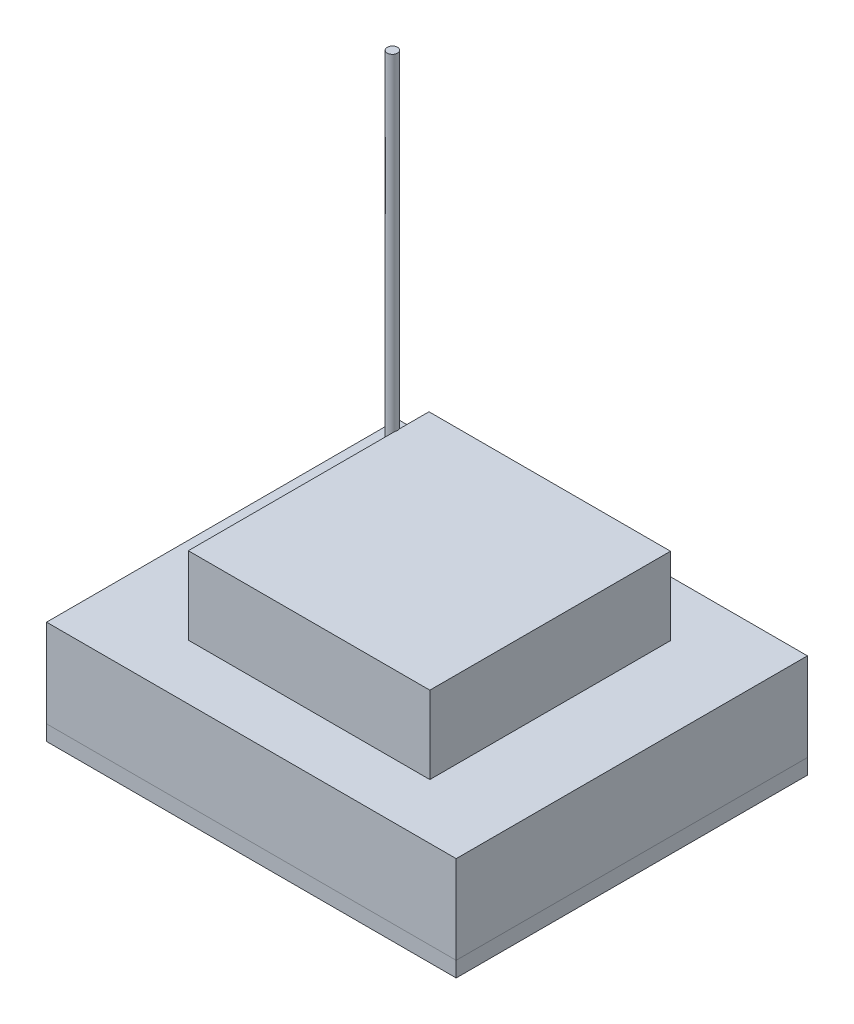
SolidWorks part; units mm, degrees
ref_plane "Front Plane" through (0, 0, 0) normal (0, 0, 1) x (1, 0, 0)
ref_plane "Top Plane" through (0, 0, 0) normal (0, 1, 0) x (1, 0, 0)
ref_plane "Right Plane" through (0, 0, 0) normal (1, 0, 0) x (0, 0, -1)
sketch "Sketch1" plane through (0, 0, 0) normal (0, 0, 1) x (1, 0, 0)
  line L1 (-509.3, -109.4835) -> (509.3, -109.4835)
  line L2 (-509.3, -109.4835) -> (-509.3, 109.4835)
  line L3 (-509.3, 109.4835) -> (509.3, 109.4835)
  line L4 (509.3, -109.4835) -> (509.3, 109.4835)
  line L5 (0, 109.4835) -> (0, -109.4835) construction
  line L6 (-509.3, 0) -> (509.3, 0) construction
  point P0 (0, 0)
  dimension "D1" = 1018.6
  dimension "D2" = 218.967
extrude "Boss-Extrude1" add sketch "Sketch1" along normal mid plane 873.5
sketch "Sketch2" plane through (0, 0, 0) normal (0, 0, 1) x (1, 0, 0)
  line L0 (509.3, 109.4835) -> (-509.3, 109.4835) construction
  line L1 (-294.3, 109.4835) -> (306.3, 109.4835)
  line L2 (-294.3, 109.4835) -> (-294.3, 302.0435)
  line L3 (-294.3, 302.0435) -> (306.3, 302.0435)
  line L4 (306.3, 109.4835) -> (306.3, 302.0435)
  line L5 (-509.3, 109.4835) -> (-509.3, -109.4835) construction
  line L6 (509.3, -109.4835) -> (509.3, 109.4835) construction
  dimension "D1" = 215
  dimension "D2" = 203
  dimension "D3" = 192.56
extrude "Boss-Extrude2" add sketch "Sketch2" along normal mid plane 598.5
sketch "Sketch3" plane through (0, 109.4835, 0) normal (0, 1, 0) x (1, 0, 0)
  line L1 (-294.3, 299.25) -> (306.3, 299.25) construction
  line L2 (-294.3, -299.25) -> (-294.3, 299.25) construction
  circle A0 centre (-306, 219.95) radius 12.7
  point P3 (-293.3, 219.95)
  dimension "D1" = 25.4
  dimension "D3" = 1
  dimension "D2" = 79.3
extrude "Boss-Extrude5" add sketch "Sketch3" along normal blind 1005.06
sketch "Sketch4" plane through (0, -109.4835, 0) normal (0, -1, 0) x (1, 0, 0)
  line L4 (-509.3, -436.75) -> (509.3, -436.75)
  line L5 (509.3, -436.75) -> (509.3, 436.75)
  line L6 (509.3, 436.75) -> (-509.3, 436.75)
  line L7 (-509.3, 436.75) -> (-509.3, -436.75)
  line L8 (-509.3, -436.75) -> (509.3, -436.75)
  line L9 (509.3, -436.75) -> (509.3, 436.75)
  line L10 (509.3, 436.75) -> (-509.3, 436.75)
  line L11 (-509.3, 436.75) -> (-509.3, -436.75)
  dimension "D1" = 0
extrude "Boss-Extrude6" add sketch "Sketch4" along normal blind 38.1 separate body
